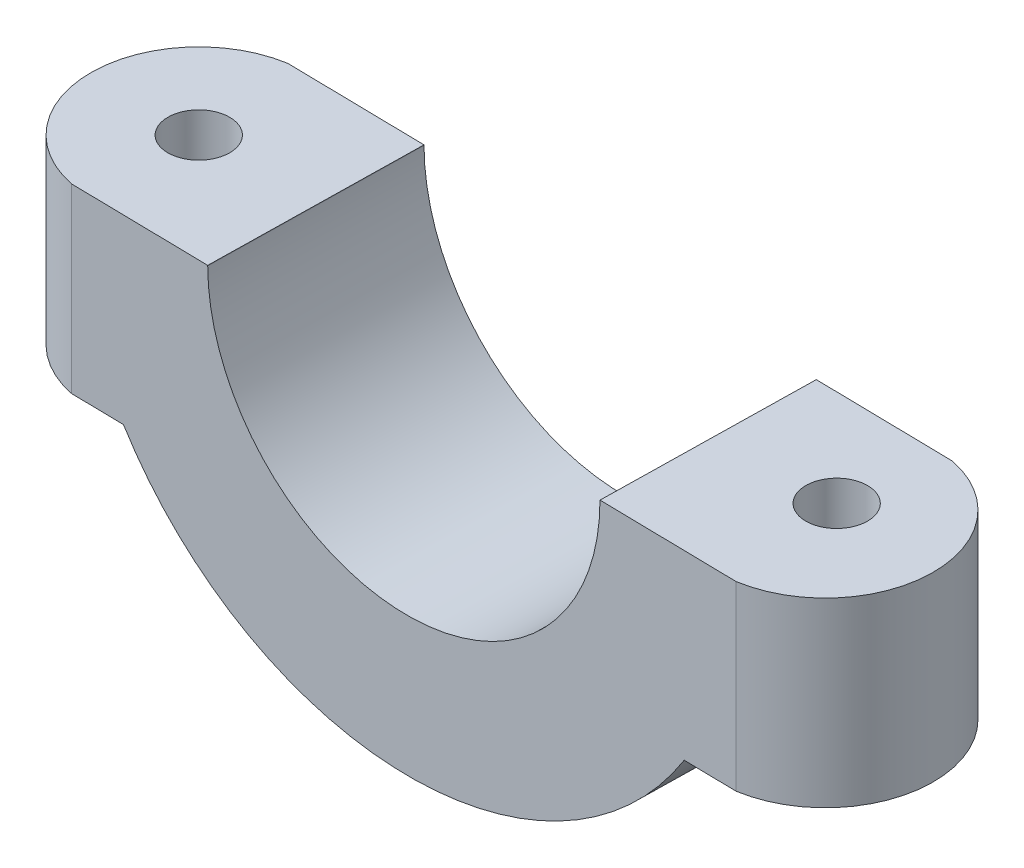
SolidWorks part; units mm, degrees
ref_plane "前视基准面" through (0, 0, 0) normal (0, 0, 1) x (1, 0, 0)
ref_plane "上视基准面" through (0, 0, 0) normal (0, 1, 0) x (1, 0, 0)
ref_plane "右视基准面" through (0, 0, 0) normal (1, 0, 0) x (0, 0, -1)
other "Configuration Table"
sketch "草图1" plane through (0, 0, 0) normal (0, 1, 0) x (1, 0, 0)
  line L5 (0, 30.5057) -> (0, -28.4144) construction
  line L6 (43.6753, 0) -> (-23.5154, 0) construction
  line L14 (10.8934, -6.0497) -> (18.5263, -6.1865)
  line L15 (11.1031, 5.652) -> (10.8934, -6.0497)
  line L16 (18.736, 5.5152) -> (11.1031, 5.652)
  line L17 (10.8934, -6.0497) -> (18.5263, -6.1865)
  line L18 (11.1031, 5.652) -> (10.8934, -6.0497)
  line L19 (18.736, 5.5152) -> (11.1031, 5.652)
  line L20 (-10.8934, 6.0461) -> (-18.5263, 6.1829)
  line L21 (-11.1031, -5.6556) -> (-10.8934, 6.0461)
  line L22 (-18.736, -5.5188) -> (-11.1031, -5.6556)
  line L23 (-10.8934, 6.0461) -> (-18.5263, 6.1829)
  line L24 (-11.1031, -5.6556) -> (-10.8934, 6.0461)
  line L25 (-18.736, -5.5188) -> (-11.1031, -5.6556)
  arc A7 (18.5263, -6.1865) -> (18.736, 5.5152) centre (17.5643, -0.3165) ccw
  arc A8 (18.5263, -6.1865) -> (18.736, 5.5152) centre (17.5643, -0.3165) ccw
  arc A9 (-18.5263, 6.1829) -> (-18.736, -5.5188) centre (-17.5643, 0.3129) ccw
  arc A10 (-18.5263, 6.1829) -> (-18.736, -5.5188) centre (-17.5643, 0.3129) ccw
  point P0 (0, 0)
  dimension "D1" = 0
  dimension "D2" = 0
extrude "凸台-拉伸1" add sketch "草图1" along normal blind 10
sketch "草图3" plane through (-0.1049, 0, 5.8526) normal (-0.0179, 0, 0.9998) x (0.9998, 0, 0.0179)
  line L0 (-11, 10) -> (-18.6342, 10)
  line L6 (0, -13.4252) -> (0, -1) construction
  line L7 (11, 10) -> (18.6342, 10)
  arc A0 (-11, 10) -> (11, 10) centre (0, 10) ccw
  arc A7 (-18.6342, 10) -> (18.6342, 10) centre (0, 10) ccw
extrude "凸台-拉伸3" add sketch "草图3" against normal up to surface (11.7036 mm away) up to face at (14.9195, 5, -5.5836)
sketch "草图5" plane through (0, 0, 0) normal (0, -1, 0) x (1, 0, 0)
  line L0 (0, 15.5077) -> (0, -17.4663) construction
  circle A0 centre (-17.5643, -0.3129) radius 1.7
  circle A1 centre (17.5643, -0.3129) radius 1.7
  dimension "D1" = 3.4
extrude "切除-拉伸1" cut sketch "草图5" against normal through all
sketch "草图6" plane through (0, 0, 0) normal (0, -1, 0) x (1, 0, 0)
  line L0 (0, 13.3381) -> (0, -11.0455) construction
  line L13 (20.3143, -1.9007) -> (17.5643, -3.4884)
  line L14 (-17.5643, -3.4884) -> (-14.8143, -1.9007)
  line L15 (-14.8143, -1.9007) -> (-14.8143, 1.2748)
  line L16 (-14.8143, 1.2748) -> (-17.5643, 2.8625)
  line L17 (-17.5643, 2.8625) -> (-20.3143, 1.2748)
  line L18 (-20.3143, 1.2748) -> (-20.3143, -1.9007)
  line L19 (-20.3143, -1.9007) -> (-17.5643, -3.4884)
  line L20 (20.3143, 1.2748) -> (20.3143, -1.9007)
  line L21 (17.5643, 2.8625) -> (20.3143, 1.2748)
  line L22 (14.8143, 1.2748) -> (17.5643, 2.8625)
  line L23 (14.8143, -1.9007) -> (14.8143, 1.2748)
  line L24 (17.5643, -3.4884) -> (14.8143, -1.9007)
  circle A0 centre (-17.5643, -0.3129) radius 2.75 construction
  dimension "D1" = 5.5
extrude "切除-拉伸2" cut sketch "草图6" against normal mid plane 4.8
